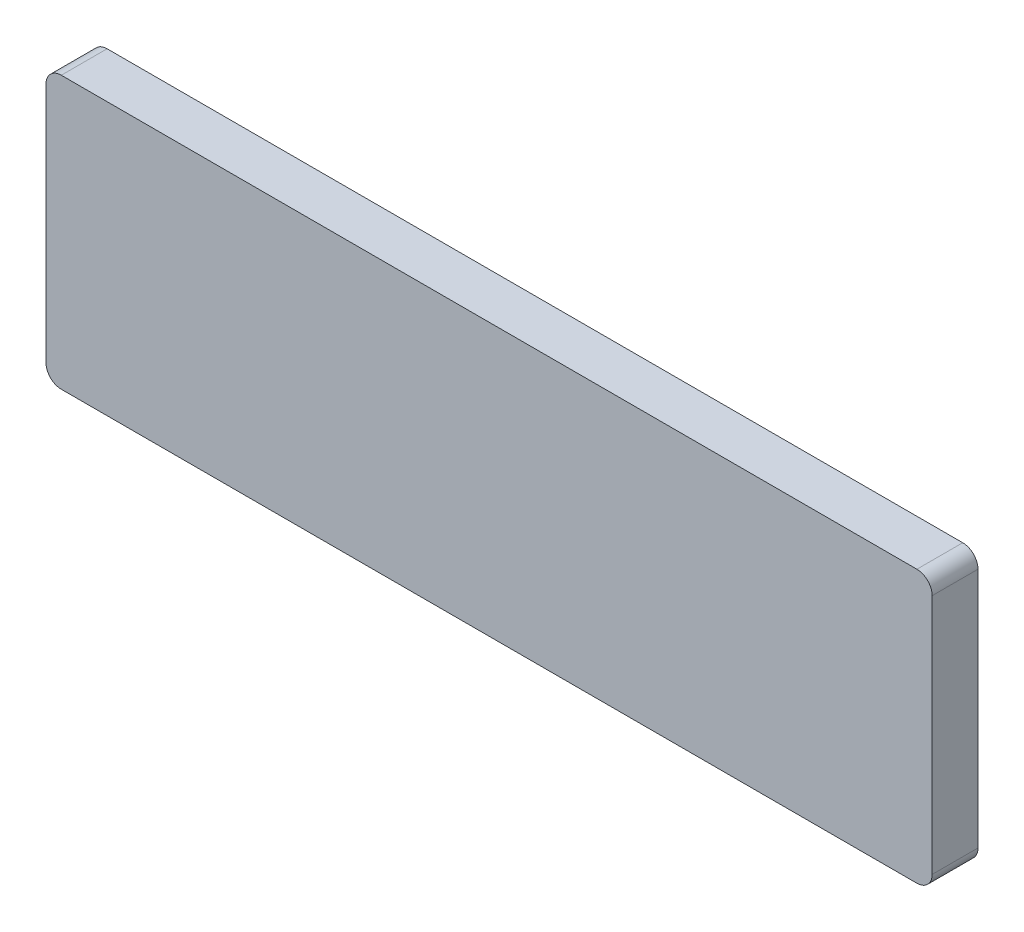
SolidWorks part; units mm, degrees
material "Cedar"
ref_plane "Plan de face" through (0, 0, 0) normal (0, 0, 1) x (1, 0, 0)
ref_plane "Plan de dessus" through (0, 0, 0) normal (0, 1, 0) x (1, 0, 0)
ref_plane "Plan de droite" through (0, 0, 0) normal (1, 0, 0) x (0, 0, -1)
sketch "Sketch1" plane through (0, 0, 0) normal (0, 0, 1) x (1, 0, 0)
  line L1 (-140, 44.5) -> (140, 44.5)
  line L2 (-145, 39.5) -> (-145, -39.5)
  line L3 (-140, -44.5) -> (140, -44.5)
  line L4 (145, 39.5) -> (145, -39.5)
  line L5 (-145, 44.5) -> (145, -44.5) construction
  line L6 (-145, -44.5) -> (145, 44.5) construction
  arc A0 (140, 44.5) -> (145, 39.5) centre (140, 39.5) cw
  arc A1 (140, -44.5) -> (145, -39.5) centre (140, -39.5) ccw
  arc A2 (-145, -39.5) -> (-140, -44.5) centre (-140, -39.5) ccw
  arc A3 (-140, 44.5) -> (-145, 39.5) centre (-140, 39.5) ccw
  point P0 (0, 0)
  dimension "D3" = 5
  dimension "D1" = 290
  dimension "D2" = 89
extrude "Boss-Extrude1" add sketch "Sketch1" along normal mid plane 15
